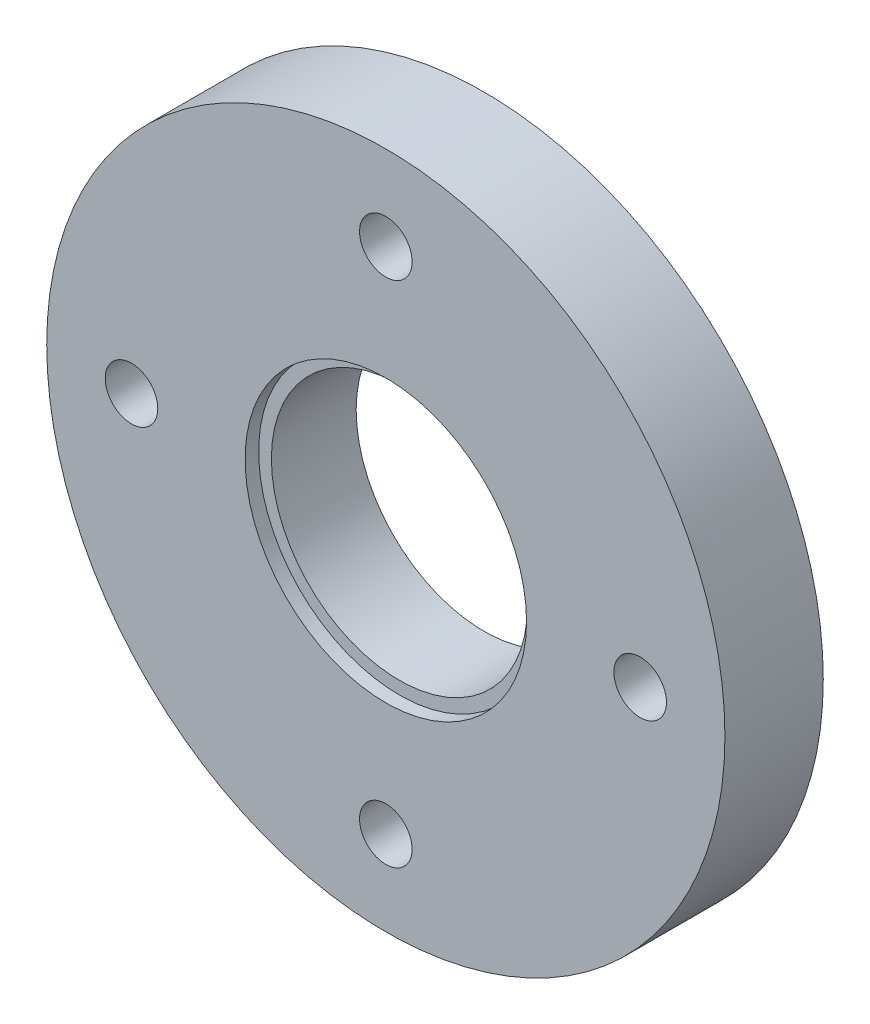
SolidWorks part; units mm, degrees
ref_plane "正面" through (0, 0, 0) normal (0, 0, 1) x (1, 0, 0)
ref_plane "平面" through (0, 0, 0) normal (0, 1, 0) x (1, 0, 0)
ref_plane "右側面" through (0, 0, 0) normal (1, 0, 0) x (0, 0, -1)
sketch "ｽｹｯﾁ1" plane through (0, 0, 0) normal (0, 0, 1) x (1, 0, 0)
  line L0 (-15, 0) -> (0, 0) construction
  line L1 (0, 0) -> (0, 15) construction
  circle A0 centre (0, 0) radius 20
  circle A1 centre (0, 0) radius 7.55
  circle A2 centre (0, 15) radius 1.55
  circle A3 centre (15, 0) radius 1.55
  circle A4 centre (0, -15) radius 1.55
  circle A5 centre (-15, 0) radius 1.55
  dimension "D1" = 15.1
  dimension "D2" = 40
  dimension "D3" = 3.1
  dimension "D4" = 15
  dimension "D5" = 4
extrude "ﾎﾞｽ - 押し出し1" add sketch "ｽｹｯﾁ1" along normal blind 5.8
sketch "ｽｹｯﾁ2" plane through (0, 0, 5.8) normal (0, 0, 1) x (1, 0, 0)
  circle A0 centre (0, 0) radius 8.3
  dimension "D1" = 16.6
extrude "ｶｯﾄ - 押し出し1" cut sketch "ｽｹｯﾁ2" against normal blind 0.8
